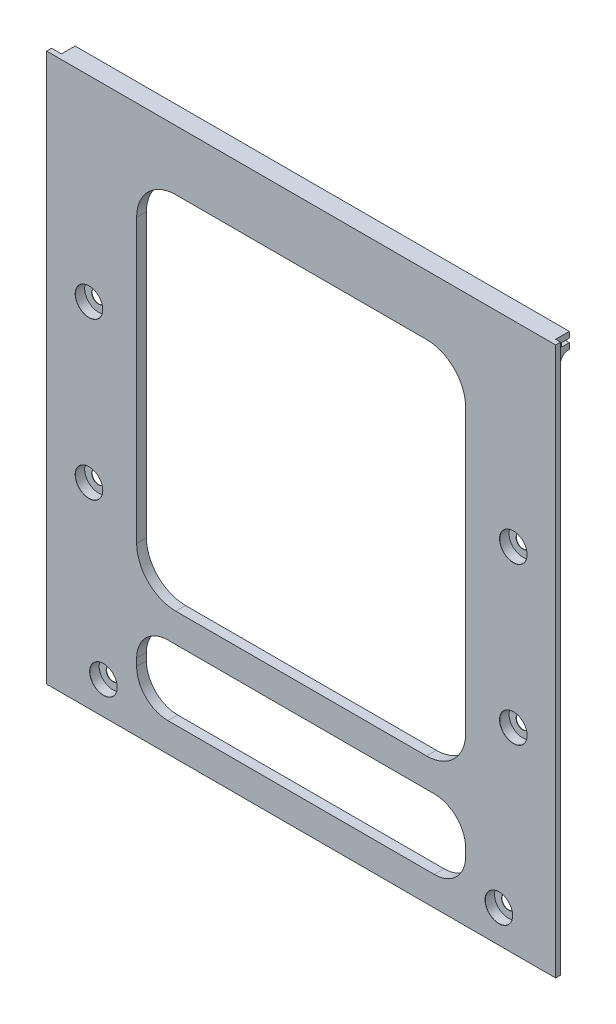
SolidWorks part; units mm, degrees
ref_plane "Plano frontal" through (0, 0, 0) normal (0, 0, 1) x (1, 0, 0)
ref_plane "Plano superior" through (0, 0, 0) normal (0, 1, 0) x (1, 0, 0)
ref_plane "Plano direito" through (0, 0, 0) normal (1, 0, 0) x (0, 0, -1)
sketch "Esboço1" plane through (0, 0, 0) normal (0, 0, 1) x (1, 0, 0)
  line L1 (-64.4893, 40.9259) -> (65.5107, 40.9259)
  line L2 (-64.4893, 40.9259) -> (-64.4893, -99.1241)
  line L3 (-64.4893, -99.1241) -> (65.5107, -99.1241)
  line L4 (65.5107, 40.9259) -> (65.5107, -99.1241)
  dimension "D1" = 130
  dimension "D2" = 140.05
extrude "Ressalto-extrusão1" add sketch "Esboço1" along normal blind 2.5
sketch "Esboço2" plane through (0, 0, 0) normal (0, 0, -1) x (-1, 0, 0)
  line L0 (64.4893, 40.9259) -> (64.4893, -99.1241) construction
  line L1 (-65.5107, 40.9259) -> (64.4893, 40.9259)
  line L2 (-65.5107, 40.9259) -> (-65.5107, 36.9259)
  line L3 (-65.5107, 36.9259) -> (64.4893, 36.9259)
  line L4 (64.4893, 40.9259) -> (64.4893, 36.9259)
  dimension "D1" = 4
extrude "Ressalto-extrusão2" add sketch "Esboço2" along normal blind 2.25
fillet "Filete1" radius 2 1 edges at (0.5107, 36.9259, 0)
sketch "Esboço3" plane through (0, 0, -2.25) normal (0, 0, -1) x (-1, 0, 0)
  line L0 (-65.5107, 40.9259) -> (-65.5107, 36.9259) construction
  line L1 (-65.5107, 39.4259) -> (64.4893, 39.4259)
  line L2 (-65.5107, 39.4259) -> (-65.5107, 38.4259)
  line L3 (-65.5107, 38.4259) -> (64.4893, 38.4259)
  line L4 (64.4893, 39.4259) -> (64.4893, 38.4259)
  line L5 (64.4893, 36.9259) -> (64.4893, 40.9259) construction
  line L6 (-65.5107, 40.9259) -> (-65.5107, 39.4259)
  line L7 (-65.5107, 38.4259) -> (-65.5107, 36.9259)
  line M7 (-65.5107, 40.9259) -> (-65.5107, 36.9259)
  line M9 (64.4893, 36.9259) -> (64.4893, 40.9259)
  dimension "D1" = 1
extrude "Corte-extrusão1" cut sketch "Esboço3" against normal blind 2 contours L3 L1 M7 M9
sketch "Esboço6" plane through (0, 0, -2.25) normal (0, 0, -1) x (-1, 0, 0)
  line L0 (64.4893, -99.1241) -> (-65.5107, -99.1241) construction
  line L1 (-65.5107, 40.9259) -> (-64.2607, 40.9259)
  line L2 (-65.5107, 40.9259) -> (-65.5107, -99.1241)
  line L3 (-65.5107, -99.1241) -> (-64.2607, -99.1241)
  line L4 (-64.2607, 40.9259) -> (-64.2607, -99.1241)
  line L5 (-0.5107, 40.9259) -> (-0.5107, -99.1241) construction
  line L6 (64.4893, 40.9259) -> (-65.5107, 40.9259) construction
  line L7 (64.4893, -99.1241) -> (63.2393, -99.1241)
  line L8 (63.2393, 40.9259) -> (63.2393, -99.1241)
  line L9 (64.4893, 40.9259) -> (63.2393, 40.9259)
  line L10 (64.4893, 40.9259) -> (64.4893, -99.1241)
  dimension "D1" = 1.25
extrude "Corte-extrusão2" cut sketch "Esboço6" against normal blind 3.5
sketch "Esboço8" plane through (0, 40.9259, 0) normal (0, 1, 0) x (1, 0, 0)
  line L1 (-63.2393, 2.25) -> (-61.9893, 2.25)
  line L2 (-63.2393, 2.25) -> (-63.2393, -1.25)
  line L3 (-63.2393, -1.25) -> (-61.9893, -1.25)
  line L4 (-61.9893, 2.25) -> (-61.9893, -1.25)
  point P5 (0, 0)
  point P6 (0, 0)
  dimension "D1" = 1.25
extrude "Corte-extrusão3" cut sketch "Esboço8" against normal blind 6.25
sketch "Esboço10" plane through (0, 0, 2.5) normal (0, 0, 1) x (1, 0, 0)
  line L0 (0.5107, 40.9259) -> (0.5107, -99.1241) construction
  line L1 (65.5107, 40.9259) -> (-64.4893, 40.9259) construction
  line L2 (-64.4893, -99.1241) -> (65.5107, -99.1241) construction
  line L3 (-53.6893, 40.9259) -> (-53.6893, -99.1241) construction
  line L4 (-64.4893, 40.9259) -> (-64.4893, -99.1241) construction
  line L5 (-64.4893, -9.1241) -> (0.5107, -9.1241) construction
  circle A0 centre (-53.6893, -9.1241) radius 1.5
  circle A1 centre (-53.6893, -49.1241) radius 1.5
  circle A2 centre (54.7107, -49.1241) radius 1.5
  circle A3 centre (54.7107, -9.1241) radius 1.5
  point P16 (-53.6893, -7.6241)
  point P17 (-53.6893, -50.6241)
  dimension "D2" = 3
  dimension "D4" = 43
  dimension "D1" = 10.8
  dimension "D3" = 50.05
hole_wizard "Rebaixo para parafuso com cabeça panela de M31" positions "Esboço11" profile "Esboço12" counterbore size "M3" standard "ISO" end condition through all
sketch "Esboço11" plane through (0, 0, 2.5) normal (0, 0, 1) x (1, 0, 0)
  point P0 (-53.6893, -9.1241)
  point P3 (-53.6893, -49.1241)
  point P6 (54.7107, -9.1241)
  point P9 (54.7107, -49.1241)
sketch "Esboço12" plane through (-53.6893, -9.1241, 2.5) normal (1, 0, 0) x (0, -1, 0)
  line L0 (0, 0) -> (0, 4.75)
  line L1 (0, 4.75) -> (1.7, 4.75)
  line L3 (1.7, 4.75) -> (1.7, 2.4)
  line L4 (3.5, 2.4) -> (1.7, 2.4)
  line L5 (3.5, 2.4) -> (3.5, 0.025)
  line L6 (3.5, 0.025) -> (3.525, 0)
  line L7 (3.525, 0) -> (0, 0)
  line L8 (-3.5, 0.025) -> (-3.525, 0) construction
  line L11 (0, -6.35) -> (0, 107.95) construction
  dimension "Thru Hole Dia." = 3.4
  dimension "Thru Hole Depth" = 4.75
  dimension "C'Bore Dia." = 7
  dimension "C'Bore Depth" = 2.4
  dimension "Near C'Sink Dia." = 7.05
  dimension "Near C'Sink Angle" = 90
sketch "Esboço13" plane through (0, 0, 2.5) normal (0, 0, 1) x (1, 0, 0)
  line L0 (0.5107, 40.9259) -> (0.5107, -99.1241) construction
  line L1 (32.536, -66.4862) -> (-31.5147, -66.4862)
  line L2 (42.536, -56.4862) -> (42.536, 15.6392)
  line L3 (32.536, 25.6392) -> (-31.5147, 25.6392)
  line L4 (-41.5147, -56.4862) -> (-41.5147, 15.6392)
  line L5 (42.536, -66.4862) -> (-41.5147, 25.6392) construction
  line L6 (42.536, 25.6392) -> (-41.5147, -66.4862) construction
  line L8 (34.536, -91.705) -> (-33.5147, -91.705)
  line L9 (42.536, -83.705) -> (42.536, -81.8806)
  line L10 (34.536, -73.8806) -> (-33.5147, -73.8806)
  line L11 (-41.5147, -83.705) -> (-41.5147, -81.8806)
  line L12 (42.536, -91.705) -> (-41.5147, -73.8806) construction
  line L13 (42.536, -73.8806) -> (-41.5147, -91.705) construction
  arc A0 (42.536, 15.6392) -> (32.536, 25.6392) centre (32.536, 15.6392) ccw
  arc A1 (32.536, -66.4862) -> (42.536, -56.4862) centre (32.536, -56.4862) ccw
  arc A2 (-31.5147, -66.4862) -> (-41.5147, -56.4862) centre (-31.5147, -56.4862) cw
  arc A3 (-31.5147, 25.6392) -> (-41.5147, 15.6392) centre (-31.5147, 15.6392) ccw
  arc A4 (34.536, -91.705) -> (42.536, -83.705) centre (34.536, -83.705) ccw
  arc A5 (42.536, -81.8806) -> (34.536, -73.8806) centre (34.536, -81.8806) ccw
  arc A6 (-33.5147, -91.705) -> (-41.5147, -83.705) centre (-33.5147, -83.705) cw
  arc A7 (-33.5147, -73.8806) -> (-41.5147, -81.8806) centre (-33.5147, -81.8806) ccw
  point P0 (0.5107, -20.4235)
  point P19 (0.5107, -82.7928)
  dimension "D1" = 10
  dimension "D2" = 8
extrude "Corte-extrusão5" cut sketch "Esboço13" against normal blind 8.25
sketch "Esboço14" plane through (0, 0, 2.5) normal (0, 0, 1) x (1, 0, 0)
  line L0 (-49.9893, -99.1241) -> (-49.9893, -75.15) construction
  line L1 (-64.4893, -99.1241) -> (65.5107, -99.1241) construction
  line L2 (-64.4893, 40.9259) -> (-64.4893, -99.1241) construction
  line L3 (0.5107, -99.1241) -> (0.5107, -90.8241) construction
  line L4 (0.5107, 40.9259) -> (0.5107, -99.1241) construction
  circle A0 centre (-49.9893, -90.8241) radius 3.7
  circle A1 centre (51.0107, -90.8241) radius 3.7
  point P8 (-49.9893, -87.1241)
  dimension "D1" = 14.5
  dimension "D2" = 8.3
hole_wizard "Rebaixo para parafuso com cabeça panela de M32" positions "Esboço15" profile "Esboço16" counterbore size "M3" standard "ISO" end condition through all
sketch "Esboço15" plane through (0, 0, 2.5) normal (0, 0, 1) x (1, 0, 0)
  point P0 (-49.9893, -90.8241)
  point P3 (51.0107, -90.8241)
sketch "Esboço16" plane through (-49.9893, -90.8241, 2.5) normal (1, 0, 0) x (0, -1, 0)
  line L0 (0, 0) -> (0, 4.75)
  line L1 (0, 4.75) -> (1.7, 4.75)
  line L3 (1.7, 4.75) -> (1.7, 2.4)
  line L4 (3.5, 2.4) -> (1.7, 2.4)
  line L5 (3.5, 2.4) -> (3.5, 0.025)
  line L6 (3.5, 0.025) -> (3.525, 0)
  line L7 (3.525, 0) -> (0, 0)
  line L8 (-3.5, 0.025) -> (-3.525, 0) construction
  line L11 (0, -6.35) -> (0, 107.95) construction
  dimension "Thru Hole Dia." = 3.4
  dimension "Thru Hole Depth" = 4.75
  dimension "C'Bore Dia." = 7
  dimension "C'Bore Depth" = 2.4
  dimension "Near C'Sink Dia." = 7.05
  dimension "Near C'Sink Angle" = 90
